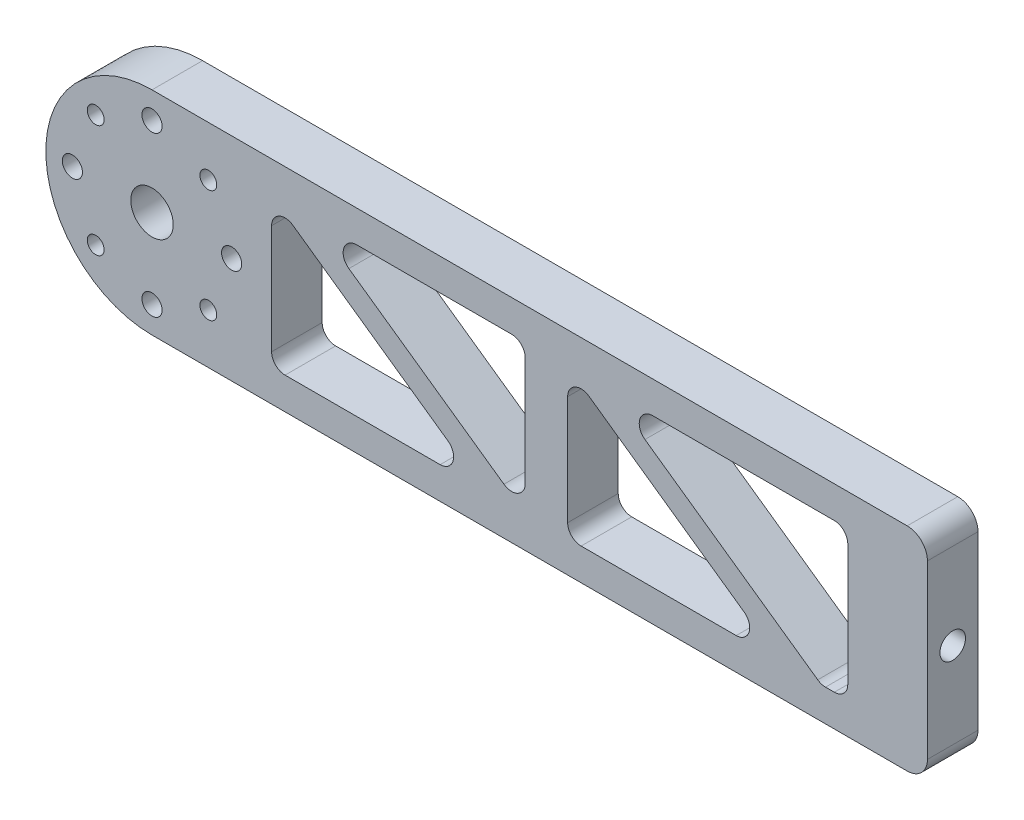
SolidWorks part; units mm, degrees
ref_plane "Front Plane" through (0, 0, 0) normal (0, 0, 1) x (1, 0, 0)
ref_plane "Top Plane" through (0, 0, 0) normal (0, 1, 0) x (1, 0, 0)
ref_plane "Right Plane" through (0, 0, 0) normal (1, 0, 0) x (0, 0, -1)
sketch "Sketch1" plane through (0, 0, 0) normal (0, 0, 1) x (1, 0, 0)
  line L0 (0, -1000) -> (0, 49000) construction
  line L1 (-73.025, 20) -> (73.025, 20)
  line L2 (-73.025, 20) -> (-73.025, -20) construction
  line L3 (-73.025, -20) -> (73.025, -20)
  line L4 (73.025, 20) -> (73.025, -20)
  line L5 (-73.025, 20) -> (73.025, -20) construction
  line L6 (-73.025, -20) -> (73.025, 20) construction
  line L7 (-1000, 0) -> (49000, 0) construction
  arc A0 (-73.025, 20) -> (-73.025, -20) centre (-73.025, 0) ccw
  circle A1 centre (-73.025, 0) radius 4
  point P0 (0, 0)
  dimension "D3" = 8
  dimension "D1" = 146.05
  dimension "D2" = 40
extrude "Boss-Extrude1" add sketch "Sketch1" along normal blind 9.525
sketch "Sketch3" plane through (0, 0, 0) normal (0, 0, 1) x (1, 0, 0)
  line L0 (-73.025, 20) -> (-73.025, -20) construction
  line L1 (-1047.73, 0) -> (48952.27, 0) construction
  line L2 (-73.025, 0) -> (-83.6316, 10.6066) construction
  circle A0 centre (-73.025, 0) radius 15 construction
  circle A1 centre (-73.025, 15) radius 1.8987
  circle A2 centre (-58.025, 0) radius 1.8986
  circle A3 centre (-73.025, -15) radius 1.8987
  circle A4 centre (-88.025, 0) radius 1.8987
  circle A5 centre (-83.6316, 10.6066) radius 1.5875
  circle A6 centre (-62.4184, 10.6066) radius 1.5875
  circle A7 centre (-62.4184, -10.6066) radius 1.5875
  circle A8 centre (-83.6316, -10.6066) radius 1.5875
  point P25 (-73.025, 0)
  point P29 (-73.025, 0)
  dimension "D1" = 30
  dimension "D2" = 3.7973
  dimension "D4" = 45
  dimension "D5" = 3.175
  dimension "D6" = 4
  dimension "D3" = 4
extrude "Cut-Extrude2" cut sketch "Sketch3" along normal through all
sketch "Sketch8" plane through (0, 0, 9.525) normal (0, 0, 1) x (1, 0, 0)
  line L1 (-50.501, 14) -> (-50.501, -14)
  line L2 (-73.025, -20) -> (73.025, -20) construction
  line L3 (73.025, 0) -> (53.025, 0) construction
  line L4 (73.025, -20) -> (73.025, 20) construction
  line L5 (53.025, 20) -> (53.025, -20) construction
  line L6 (73.025, 20) -> (-73.025, 20) construction
  line L7 (-50.393, 0) -> (53.025, 0) construction
  line L8 (1.262, -20) -> (1.262, -14) construction
  line L9 (1.262, 20) -> (1.262, 14) construction
  line L10 (1.262, -14) -> (-2.738, -14) construction
  line L11 (-50.501, 14) -> (-42.501, 14) construction
  line L12 (-2.738, -14) -> (-10.738, -14) construction
  line L13 (-50.501, -14) -> (-10.738, -14)
  line L14 (-10.738, -14) -> (-50.501, 14)
  line L15 (-42.501, 14) -> (-2.738, -14)
  line L16 (-2.738, -14) -> (-2.738, 14)
  line L17 (-2.738, 14) -> (-42.501, 14)
  line L18 (1.262, -14) -> (5.262, -14) construction
  line L19 (53.025, 14) -> (13.262, 14)
  line L20 (45.025, -14) -> (5.262, 14)
  line L21 (13.262, 14) -> (53.025, -14)
  line L23 (5.262, -14) -> (45.025, -14)
  line L24 (5.262, 14) -> (5.262, -14)
  line L25 (53.025, 14) -> (58.025, 14)
  line L26 (58.025, 14) -> (58.025, -14)
  line L27 (58.025, -14) -> (53.025, -14)
  circle A1 centre (-58.025, 0) radius 1.8987 construction
  dimension "D1" = 7.524
  dimension "D2" = 20
  dimension "D3" = 6
  dimension "D4" = 6
  dimension "D5" = 8
  dimension "D6" = 4
  dimension "D7" = 4
  dimension "D8" = 5
extrude "Cut-Extrude6" cut sketch "Sketch8" against normal through all
fillet "Fillet1" radius 2.54 13 edges at (13.262, 14, 4.7625) (58.025, 14, 4.7625) (58.025, -14, 4.7625) (53.025, -14, 4.7625) (45.025, -14, 4.7625) (5.262, -14, 4.7625) (5.262, 14, 4.7625) (-2.738, -14, 4.7625) (-2.738, 14, 4.7625) (-42.501, 14, 4.7625) (-50.501, 14, 4.7625) (-50.501, -14, 4.7625) (-10.738, -14, 4.7625)
sketch "Sketch18" plane through (73.025, 0, 0) normal (1, 0, 0) x (0, 0, -1)
  line L0 (0, -20) -> (-9.525, 20) construction
  circle A0 centre (-4.7625, 0) radius 2.413
  dimension "D1" = 4.826
extrude "Cut-Extrude10" cut sketch "Sketch18" against normal up to next
fillet "Fillet2" radius 3.81 2 edges at (73.025, 20, 4.7625) (73.025, -20, 4.7625)
